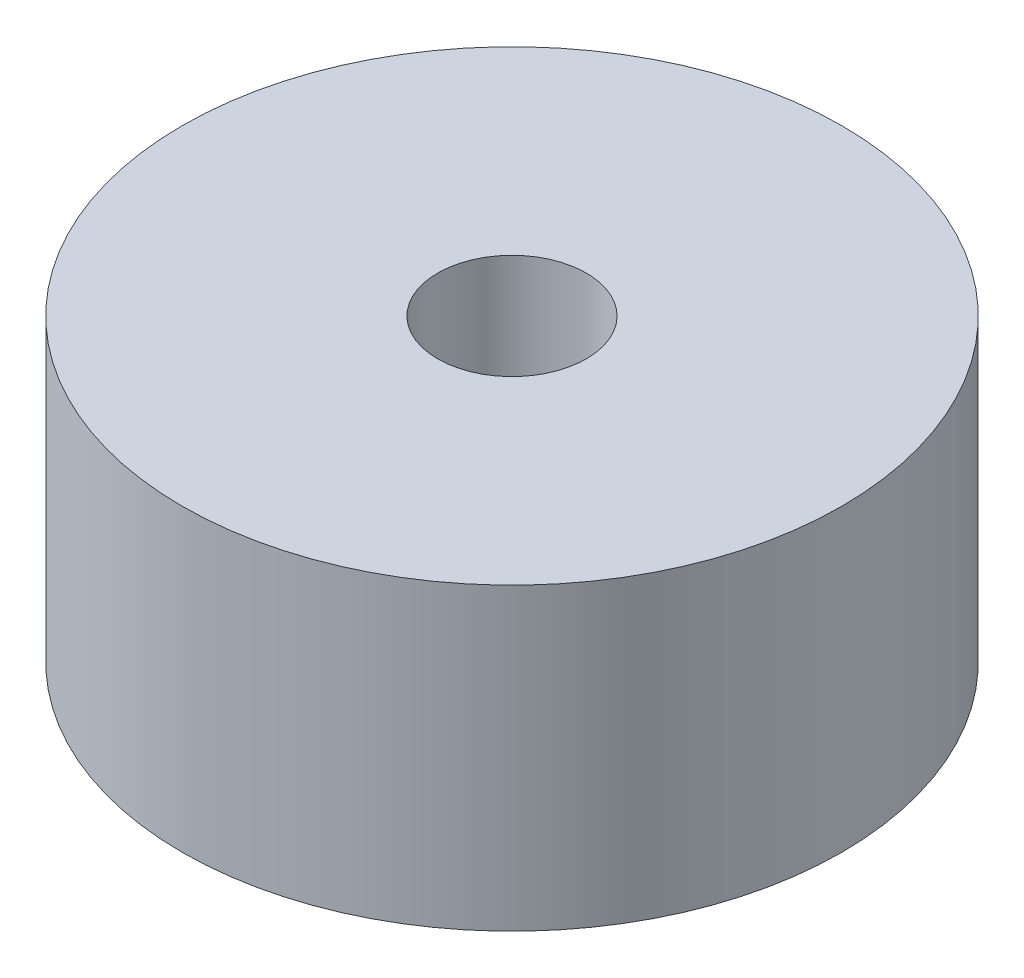
SolidWorks part; units mm, degrees
ref_plane "Front Plane" through (0, 0, 0) normal (0, 0, 1) x (1, 0, 0)
ref_plane "Top Plane" through (0, 0, 0) normal (0, 1, 0) x (1, 0, 0)
ref_plane "Right Plane" through (0, 0, 0) normal (1, 0, 0) x (0, 0, -1)
sketch "Sketch1" plane through (0, 0, 0) normal (0, 1, 0) x (1, 0, 0)
  line L0 (0, 0) -> (99.948, 0) construction
  circle A1 centre (0, 0) radius 1.24
  circle A2 centre (0, 0) radius 5.5
  dimension "D1" = 2.48
  dimension "D2" = 11
extrude "Boss-Extrude1" add sketch "Sketch1" along normal blind 5
